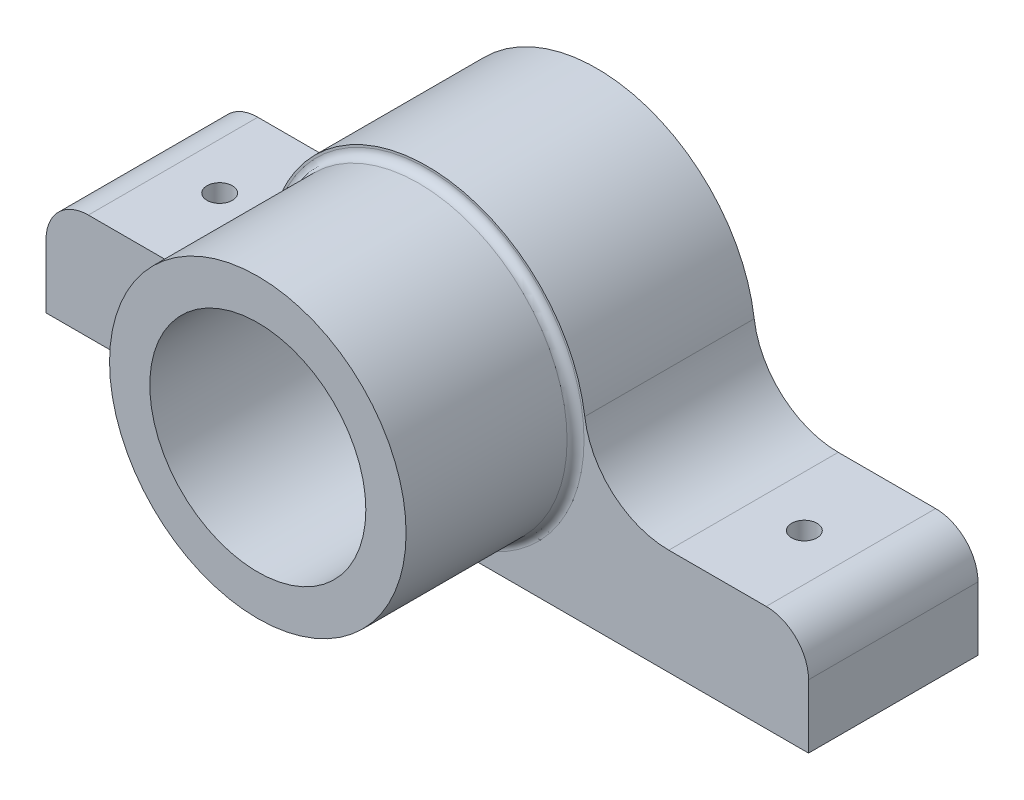
SolidWorks part; units mm, degrees
ref_plane "Front Plane" through (0, 0, 0) normal (0, 0, 1) x (1, 0, 0)
ref_plane "Top Plane" through (0, 0, 0) normal (0, 1, 0) x (1, 0, 0)
ref_plane "Right Plane" through (0, 0, 0) normal (1, 0, 0) x (0, 0, -1)
sketch "Sketch1" plane through (0, 0, 0) normal (0, 0, 1) x (1, 0, 0)
  line L0 (6.35, 4.7625) -> (70.2996, 4.7625) construction
  line L1 (0, 0) -> (76.6496, 0)
  line L2 (0, 9.525) -> (0, 0) construction
  line L3 (0, 9.525) -> (76.6496, 9.525) construction
  line L4 (76.6496, 9.525) -> (76.6496, 0) construction
  line L5 (0, 9.525) -> (0, 3.175) construction
  line L6 (0, 3.175) -> (-5.08, 3.175)
  line L7 (-5.08, 3.175) -> (-5.08, 0)
  line L8 (-5.08, 0) -> (0, 0)
  line L9 (76.6496, 9.525) -> (76.6496, 3.175) construction
  line L10 (76.6496, 3.175) -> (81.7296, 3.175)
  line L11 (81.7296, 3.175) -> (81.7296, 0)
  line L12 (81.7296, 0) -> (76.6496, 0)
  line L13 (0, 3.175) -> (1.5875, 3.175)
  line L14 (6.35, 9.525) -> (6.35, 0) construction
  line L15 (1.5875, 3.175) -> (1.5875, 4.7625)
  line L16 (75.0621, 4.7625) -> (75.0621, 3.175)
  line L17 (75.0621, 3.175) -> (76.6496, 3.175)
  line L18 (70.2996, 4.7625) -> (75.0621, 4.7625) construction
  line L19 (70.2996, 9.525) -> (70.2996, 4.7625) construction
  line L20 (11.1125, 4.7625) -> (11.1125, 3.175)
  line L21 (11.1125, 3.175) -> (65.5371, 3.175)
  line L22 (65.5371, 3.175) -> (65.5371, 4.7625)
  line L23 (6.35, 4.7625) -> (1.5875, 4.7625) construction
  circle A0 centre (6.35, 4.7625) radius 3.175 construction
  circle A1 centre (70.2996, 4.7625) radius 3.175 construction
  circle A2 centre (6.35, 4.7625) radius 0.635
  circle A3 centre (70.2996, 4.7625) radius 0.635
  circle A4 centre (6.35, 4.7625) radius 4.7625 construction
  circle A5 centre (70.2996, 4.7625) radius 4.7625 construction
  arc A6 (1.5875, 4.7625) -> (11.1125, 4.7625) centre (6.35, 4.7625) cw
  arc A7 (75.0621, 4.7625) -> (65.5371, 4.7625) centre (70.2996, 4.7625) ccw
  point P18 (38.3248, 4.7625)
  dimension "D1" = 6.35
  dimension "D2" = 6.35
  dimension "D11" = 1.27
  dimension "D3" = 5.08
  dimension "D4" = 3.175
  dimension "D5" = 3.175
  dimension "D6" = 5.08
  dimension "D7" = 6.35
  dimension "D8" = 63.9496
  dimension "D9" = 6.35
  dimension "D10" = 6.35
extrude "Boss-Extrude1" add sketch "Sketch1" along normal blind 5.08
sketch "Sketch2" plane through (0, 0, 5.08) normal (0, 0, 1) x (1, 0, 0)
  circle A0 centre (6.35, 4.7625) radius 4.445
  circle A1 centre (70.2996, 4.7625) radius 4.445
  circle A2 centre (6.35, 4.7625) radius 0.635 construction
  circle A3 centre (70.2996, 4.7625) radius 0.635 construction
  circle A4 centre (6.35, 4.7625) radius 0.635
  circle A5 centre (70.2996, 4.7625) radius 0.635
  dimension "D1" = 8.89
  dimension "D2" = 8.89
extrude "Boss-Extrude2" add sketch "Sketch2" along normal blind 5.08
sketch "Sketch3" plane through (0, 0, 10.16) normal (0, 0, 1) x (1, 0, 0)
  circle A0 centre (6.35, 4.7625) radius 3.2385
  circle A1 centre (70.2996, 4.7625) radius 3.2385
  dimension "D1" = 6.477
  dimension "D2" = 6.477
extrude "Cut-Extrude1" cut sketch "Sketch3" against normal blind 6.35
fillet "Fillet1" radius 0.254 2 edges at (74.7446, 4.7625, 5.08) (10.795, 4.7625, 5.08)
fillet "Fillet2" radius 2.54 4 edges at (75.0621, 3.175, 2.54) (11.1125, 3.175, 2.54) (65.5371, 3.175, 2.54) (1.5875, 3.175, 2.54)
fillet "Fillet3" radius 1.27 2 edges at (81.7296, 3.175, 2.54) (-5.08, 3.175, 2.54)
sketch "Sketch5" plane through (0, 3.175, 0) normal (0, 1, 0) x (1, 0, 0)
  line L0 (15.113, -2.54) -> (38.3248, -2.54) construction
  line L1 (6.35, -10.16) -> (6.35, 0) construction
  line L2 (1.905, -10.16) -> (10.795, -10.16) construction
  line L3 (-5.08, -2.54) -> (81.7296, -2.54) construction
  line L4 (-5.08, -5.08) -> (-5.08, 0) construction
  line L5 (81.7296, 0) -> (81.7296, -5.08) construction
  line L6 (38.3248, -2.54) -> (61.5366, -2.54) construction
  line L7 (11.0718, 0) -> (1.6282, 0) construction
  line L8 (70.2996, -10.16) -> (70.2996, 0) construction
  line L9 (65.8546, -10.16) -> (74.7446, -10.16) construction
  line L10 (75.0214, 0) -> (65.5778, 0) construction
  circle A0 centre (-2.413, -2.54) radius 0.381
  circle A2 centre (79.0626, -2.54) radius 0.381
  circle A3 centre (61.5366, -2.54) radius 0.381
  circle A4 centre (15.113, -2.54) radius 0.381
  dimension "D1" = 0.762
  dimension "D2" = 2.667
  dimension "D3" = 8.763
  dimension "D4" = 8.763
  dimension "D5" = 8.763
  dimension "D6" = 8.763
extrude "Cut-Extrude3" cut sketch "Sketch5" against normal through all
sketch "Sketch7" plane through (0, 3.175, 0) normal (0, 1, 0) x (1, 0, 0)
  line L0 (-5.08, -5.08) -> (-5.08, 0) construction
  line L1 (-5.08, -5.08) -> (-5.08, 0) construction
  line L2 (17.78, 0) -> (17.78, -5.08) construction
  line L3 (63.0595, 0) -> (13.5901, 0) construction
  line L4 (63.0595, -5.08) -> (13.5901, -5.08) construction
  line L5 (81.7296, 0) -> (81.7296, -5.08) construction
  line L6 (17.78, 0) -> (83.1376, 0)
  line L7 (17.78, 0) -> (17.78, -10.6123)
  line L8 (17.78, -10.6123) -> (83.1376, -10.6123)
  line L9 (83.1376, 0) -> (83.1376, -10.6123)
  line L10 (65.8546, -10.16) -> (74.7446, -10.16) construction
  circle A0 centre (-2.413, -2.54) radius 0.381 construction
  circle A1 centre (-2.413, -2.54) radius 0.381 construction
  circle A2 centre (15.113, -2.54) radius 0.381 construction
  circle A3 centre (15.113, -2.54) radius 0.381 construction
  dimension "D1" = 2.667
  dimension "D2" = 2.667
  dimension "D3" = 1.408
  dimension "D4" = 0.4523
extrude "Cut-Extrude4" cut sketch "Sketch7" against normal through all and the other way through all
fillet "Fillet4" radius 1.27 1 edges at (17.78, 3.175, 2.54)
equation "\"D2@Sketch2\"=\"D1@Sketch2\""
equation "\"D3@Sketch5\"=\"D5@Sketch5\""
equation "\"D4@Sketch5\"=\"D5@Sketch5\""
equation "\"D6@Sketch5\"=\"D5@Sketch5\""
equation "\"D2@Sketch7\"=\"D1@Sketch7\""
